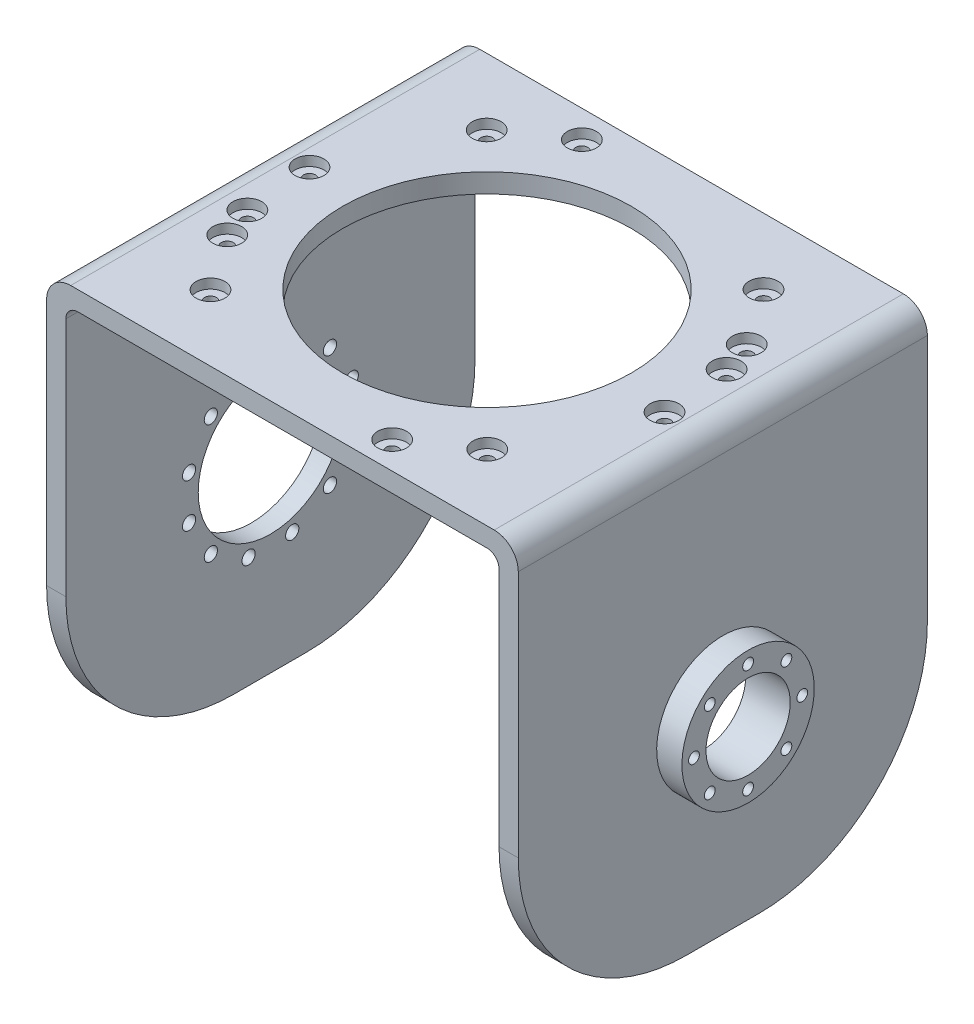
SolidWorks part; units mm, degrees
material "6061 合金"
ref_plane "前视基准面" through (0, 0, 0) normal (0, 0, 1) x (1, 0, 0)
ref_plane "上视基准面" through (0, 0, 0) normal (0, 1, 0) x (1, 0, 0)
ref_plane "右视基准面" through (0, 0, 0) normal (1, 0, 0) x (0, 0, -1)
other "Configuration Table"
sketch "草图1" plane through (0, 0, 0) normal (0, 0, 1) x (1, 0, 0)
  line L0 (-180, 0) -> (0, 0)
  line L1 (0, 0) -> (0, -175)
  line L3 (8, -175) -> (8, 8)
  line L4 (8, 8) -> (-180, 8)
  line L6 (0, -175) -> (8, -175)
  line L12 (-180, 8) -> (-188, 8)
  line L13 (-180, 0) -> (-180, -175)
  line L14 (-180, -175) -> (-188, -175)
  line L15 (-188, 8) -> (-188, -175)
  dimension "D1" = 8
  dimension "D2" = 8
  dimension "D4" = 180
  dimension "D5" = 183
  dimension "D6" = 8
  dimension "D8" = 8
extrude "凸台-拉伸1" add sketch "草图1" along normal blind 170
sketch "草图2" plane through (0, 8, 0) normal (0, 1, 0) x (1, 0, 0)
  line L0 (-216.3195, -85) -> (51.5119, -85) construction
  line L1 (8, -170) -> (-188, -170) construction
  line L2 (8, 0) -> (-188, 0) construction
  line L7 (-90, -75.3242) -> (-90, -92.2023) construction
  line L8 (8, -170) -> (8, 0) construction
  line L9 (-188, -170) -> (-188, 0) construction
  circle A2 centre (-90, -85) radius 60
  dimension "D3" = 120
extrude "切除-拉伸1" cut sketch "草图2" against normal blind 180 contours A2 L0 | L0 A2
sketch "草图3" plane through (8, 0, 0) normal (1, 0, 0) x (0, 0, -1)
  line L0 (-85, 25.6845) -> (-85, -173.3318) construction
  line L1 (0, -175) -> (0, 8) construction
  line L2 (-170, -175) -> (-170, 8) construction
  line L3 (-170, -175) -> (0, -175) construction
  line L4 (0, 0) -> (-209.686, 0) construction
  circle A0 centre (-85, -95) radius 17.5
  dimension "D1" = 35
  dimension "D2" = 80
extrude "切除-拉伸2" cut sketch "草图3" against normal through all both and the other way through all contours A0
fillet "圆角1" radius 70 4 edges at (-184, -175, 170) (-184, -175, 0) (4, -175, 0) (4, -175, 170)
fillet "圆角2" radius 5 2 edges at (-180, 0, 85) (0, 0, 85)
fillet "圆角3" radius 10 2 edges at (8, 8, 85) (-188, 8, 85)
sketch "草图6" plane through (-188, 0, 0) normal (-1, 0, 0) x (0, 0, 1)
  circle A0 centre (85, -95) radius 30
  dimension "D1" = 60
extrude "切除-拉伸6" cut sketch "草图6" against normal blind 39
sketch "草图7" plane through (0, 0, 0) normal (-1, 0, 0) x (0, 0, 1)
  circle A0 centre (85, -95) radius 13
  dimension "D1" = 26
extrude "切除-拉伸7" [suppressed] cut sketch "草图7" against normal blind 0.7
sketch "草图8" plane through (8, 0, 0) normal (1, 0, 0) x (0, 0, -1)
  line L0 (-85, -95) -> (-13.3452, -95) construction
  line L1 (-85, -95) -> (-143.0331, -95) construction
  circle A0 centre (-55, -95) radius 2.5
  circle A1 centre (-115, -95) radius 2.5
  dimension "D1" = 5
  dimension "D2" = 5
  dimension "D3" = 30
  dimension "D4" = 30
extrude "切除-拉伸8" [suppressed] cut sketch "草图8" against normal blind 10
sketch "草图9" [suppressed] plane through (8, 0, 0) normal (1, 0, 0) x (0, 0, -1)
  circle A0 centre (-55, -95) radius 6
  circle A1 centre (-115, -95) radius 6
  dimension "D1" = 12
  dimension "D2" = 12
extrude "切除-拉伸9" [suppressed] cut sketch "草图9" against normal blind 4
sketch "草图10" plane through (0, 0, 0) normal (0, -1, 0) x (1, 0, 0)
  arc A0 (-173.1989, 76.7742) -> (-168.6673, 78.8872) centre (-170.9331, 77.8307) ccw construction
  arc A1 (-149.7806, 26.5535) -> (-145.249, 28.6665) centre (-147.5148, 27.61) ccw construction
  arc A2 (-126.5235, 10.2687) -> (-121.992, 12.3818) centre (-124.2577, 11.3252) ccw construction
  arc A3 (-113.38, 5.4849) -> (-108.8485, 7.598) centre (-111.1143, 6.5414) ccw construction
  arc A4 (-85.0965, 3.0104) -> (-80.5649, 5.1235) centre (-82.8307, 4.0669) ccw construction
  arc A5 (-34.8758, 26.4287) -> (-30.3442, 28.5418) centre (-32.61, 27.4852) ccw construction
  arc A6 (-13.8072, 62.8292) -> (-9.2756, 64.9423) centre (-11.5414, 63.8857) ccw construction
  arc A7 (-18.591, 49.6857) -> (-14.0595, 51.7988) centre (-16.3252, 50.7423) ccw construction
  arc A8 (-6.8011, 93.2258) -> (-11.3327, 91.1128) centre (-9.0669, 92.1693) ccw construction
  arc A9 (-30.2194, 143.4465) -> (-34.751, 141.3335) centre (-32.4852, 142.39) ccw construction
  arc A10 (-53.4765, 159.7313) -> (-58.008, 157.6182) centre (-55.7423, 158.6748) ccw construction
  arc A11 (-66.62, 164.5151) -> (-71.1515, 162.402) centre (-68.8857, 163.4586) ccw construction
  arc A12 (-94.9035, 166.9896) -> (-99.4351, 164.8765) centre (-97.1693, 165.9331) ccw construction
  arc A13 (-145.1242, 143.5713) -> (-149.6558, 141.4582) centre (-147.39, 142.5148) ccw construction
  arc A14 (-161.409, 120.3143) -> (-165.9405, 118.2012) centre (-163.6748, 119.2577) ccw construction
  arc A15 (-166.1928, 107.1708) -> (-170.7244, 105.0577) centre (-168.4586, 106.1143) ccw construction
  arc A16 (-173.1989, 76.7742) -> (-168.6673, 78.8872) centre (-170.9331, 77.8307) ccw construction
  arc A17 (-149.7806, 26.5535) -> (-145.249, 28.6665) centre (-147.5148, 27.61) ccw construction
  arc A18 (-126.5235, 10.2687) -> (-121.992, 12.3818) centre (-124.2577, 11.3252) ccw construction
  arc A19 (-113.38, 5.4849) -> (-108.8485, 7.598) centre (-111.1143, 6.5414) ccw construction
  arc A20 (-85.0965, 3.0104) -> (-80.5649, 5.1235) centre (-82.8307, 4.0669) ccw construction
  arc A21 (-34.8758, 26.4287) -> (-30.3442, 28.5418) centre (-32.61, 27.4852) ccw construction
  arc A22 (-13.8072, 62.8292) -> (-9.2756, 64.9423) centre (-11.5414, 63.8857) ccw construction
  arc A23 (-18.591, 49.6857) -> (-14.0595, 51.7988) centre (-16.3252, 50.7423) ccw construction
  arc A24 (-6.8011, 93.2258) -> (-11.3327, 91.1128) centre (-9.0669, 92.1693) ccw construction
  arc A25 (-30.2194, 143.4465) -> (-34.751, 141.3335) centre (-32.4852, 142.39) ccw construction
  arc A26 (-53.4765, 159.7313) -> (-58.008, 157.6182) centre (-55.7423, 158.6748) ccw construction
  arc A27 (-66.62, 164.5151) -> (-71.1515, 162.402) centre (-68.8857, 163.4586) ccw construction
  arc A28 (-94.9035, 166.9896) -> (-99.4351, 164.8765) centre (-97.1693, 165.9331) ccw construction
  arc A29 (-145.1242, 143.5713) -> (-149.6558, 141.4582) centre (-147.39, 142.5148) ccw construction
  arc A30 (-161.409, 120.3143) -> (-165.9405, 118.2012) centre (-163.6748, 119.2577) ccw construction
  arc A31 (-166.1928, 107.1708) -> (-170.7244, 105.0577) centre (-168.4586, 106.1143) ccw construction
  circle A32 centre (-32.4852, 142.39) radius 2.5
  circle A33 centre (-55.7423, 158.6748) radius 2.5
  circle A34 centre (-68.8857, 163.4586) radius 2.5
  circle A35 centre (-147.39, 142.5148) radius 2.5
  circle A36 centre (-163.6748, 119.2577) radius 2.5
  circle A37 centre (-168.4586, 106.1143) radius 2.5
  circle A38 centre (-170.9331, 77.8307) radius 2.5
  circle A40 centre (-147.5148, 27.61) radius 2.5
  circle A41 centre (-124.2577, 11.3252) radius 2.5
  circle A42 centre (-111.1143, 6.5414) radius 2.5
  circle A44 centre (-32.61, 27.4852) radius 2.5
  circle A45 centre (-16.3252, 50.7423) radius 2.5
  circle A46 centre (-11.5414, 63.8857) radius 2.5
  circle A47 centre (-9.0669, 92.1693) radius 2.5
  dimension "D1" = 5
extrude "切除-拉伸10" cut sketch "草图10" against normal blind 10 contours A33 | A32 | A47 | A46 | A45 | A44 | A41 | A40 | A38 | A37 | A36 | A35
sketch "草图11" plane through (0, 8, 0) normal (0, 1, 0) x (1, 0, 0)
  circle A1 centre (-32.61, -27.4852) radius 6
  circle A2 centre (-16.3252, -50.7423) radius 6
  circle A3 centre (-11.5414, -63.8857) radius 6
  circle A4 centre (-9.0669, -92.1693) radius 6
  circle A5 centre (-32.4852, -142.39) radius 6
  circle A6 centre (-55.7423, -158.6748) radius 6
  circle A8 centre (-147.39, -142.5148) radius 6
  circle A9 centre (-163.6748, -119.2577) radius 6
  circle A10 centre (-168.4586, -106.1143) radius 6
  circle A11 centre (-170.9331, -77.8307) radius 6
  circle A12 centre (-147.5148, -27.61) radius 6
  circle A13 centre (-124.2577, -11.3252) radius 6
  circle M2 centre (-55.7423, -158.6748) radius 2.5
  circle M4 centre (-147.39, -142.5148) radius 2.5
  circle M5 centre (-163.6748, -119.2577) radius 2.5
  circle M6 centre (-168.4586, -106.1143) radius 2.5
  circle M7 centre (-170.9331, -77.8307) radius 2.5
  circle M8 centre (-147.5148, -27.61) radius 2.5
  circle M9 centre (-124.2577, -11.3252) radius 2.5
  circle M11 centre (-32.61, -27.4852) radius 2.5
  circle M12 centre (-16.3252, -50.7423) radius 2.5
  circle M13 centre (-11.5414, -63.8857) radius 2.5
  circle M14 centre (-9.0669, -92.1693) radius 2.5
  circle M15 centre (-32.4852, -142.39) radius 2.5
  dimension "D1" = 12
extrude "切除-拉伸11" cut sketch "草图11" against normal blind 4 contours A5 M15 | A6 M2 | A8 M4 | A9 M5 | A10 M6 | A11 M7 | A12 M8 | A13 M9 | A1 M11 | A2 M12 | A3 M13 | A4 M14
sketch "草图12" plane through (-188, 0, 0) normal (-1, 0, 0) x (0, 0, 1)
  line L0 (85, -95) -> (85, -143.8801) construction
  line L1 (85, -95) -> (97.9809, -143.4455) construction
  circle A0 centre (94.0587, -128.8074) radius 2.75
  circle A1 centre (75.9413, -128.8074) radius 2.75
  circle A2 centre (60.2513, -119.7487) radius 2.75
  circle A3 centre (51.1926, -104.0587) radius 2.75
  circle A4 centre (51.1926, -85.9413) radius 2.75
  circle A5 centre (60.2513, -70.2513) radius 2.75
  circle A6 centre (75.9413, -61.1926) radius 2.75
  circle A7 centre (94.0587, -61.1926) radius 2.75
  circle A8 centre (109.7487, -70.2513) radius 2.75
  circle A9 centre (118.8074, -85.9413) radius 2.75
  circle A10 centre (118.8074, -104.0587) radius 2.75
  circle A11 centre (109.7487, -119.7487) radius 2.75
  point P31 (85, -95)
  dimension "D2" = 5.5
  dimension "D1" = 15
  dimension "D3" = 35
  dimension "D4" = 12
extrude "切除-拉伸12" cut sketch "草图12" against normal blind 10
sketch "草图14" plane through (8, 0, 0) normal (1, 0, 0) x (0, 0, -1)
  circle A0 centre (-85, -95) radius 27.5
  circle A1 centre (-85, -95) radius 17.5 construction
  circle A2 centre (-85, -95) radius 17.5
  dimension "D1" = 55
extrude "凸台-拉伸2" add sketch "草图14" along normal blind 10.5
sketch "草图13" plane through (8, 0, 0) normal (1, 0, 0) x (0, 0, -1)
  line L0 (-85, -95) -> (-85, -50) construction
  circle A0 centre (-85, -95) radius 22.5 construction
  circle A1 centre (-85, -72.5) radius 2.25
  circle A2 centre (-69.0901, -79.0901) radius 2.25
  circle A3 centre (-62.5, -95) radius 2.25
  circle A4 centre (-69.0901, -110.9099) radius 2.25
  circle A5 centre (-85, -117.5) radius 2.25
  circle A6 centre (-100.9099, -110.9099) radius 2.25
  circle A7 centre (-107.5, -95) radius 2.25
  circle A8 centre (-100.9099, -79.0901) radius 2.25
  point P22 (-85, -95)
  dimension "D1" = 45
  dimension "D2" = 4.5
  dimension "D3" = 8
extrude "切除-拉伸13" cut sketch "草图13" against normal mid plane 30
